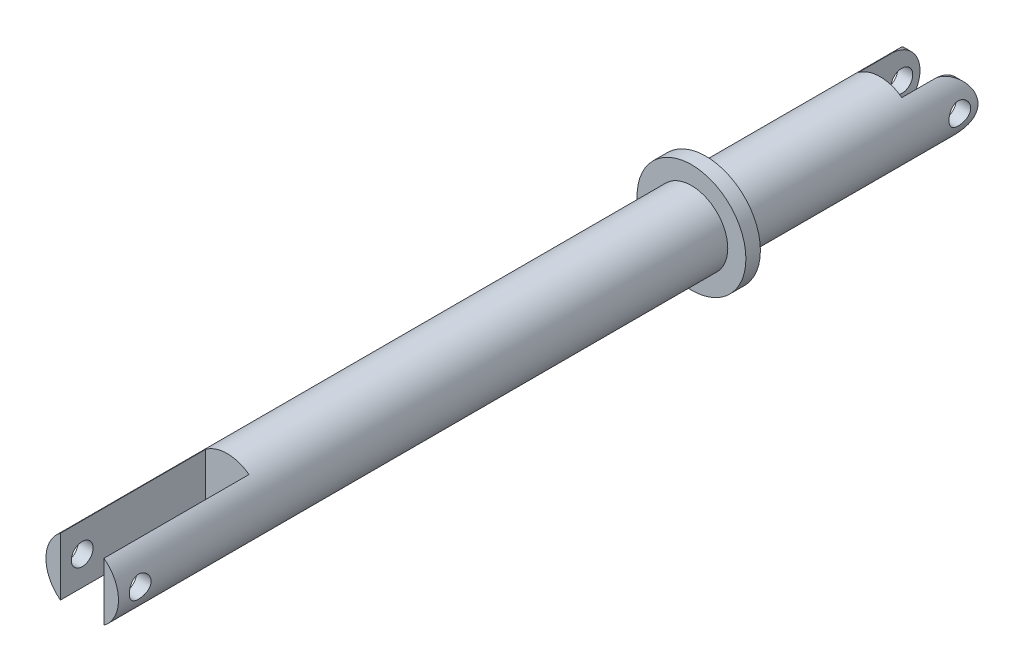
SolidWorks part; units mm, degrees
material "AISI 4340 Acero normalizado"
ref_plane "Alzado" through (0, 0, 0) normal (0, 0, 1) x (1, 0, 0)
ref_plane "Planta" through (0, 0, 0) normal (0, 1, 0) x (1, 0, 0)
ref_plane "Vista lateral" through (0, 0, 0) normal (1, 0, 0) x (0, 0, -1)
sketch "Croquis1" plane through (0, 0, 0) normal (0, 0, 1) x (1, 0, 0)
  circle A0 centre (0, 0) radius 2.5
extrude "Saliente-Extruir1" add sketch "Croquis1" along normal blind 60
ref_plane "Plano1" through (0, 0, 18) normal (0, 0, 1) x (1, 0, 0)
sketch "Croquis2" plane through (0, 0, 18) normal (0, 0, 1) x (1, 0, 0)
  circle A0 centre (0, 0) radius 2.5
  circle A1 centre (0, 0) radius 3.75
extrude "Saliente-Extruir2" add sketch "Croquis2" against normal blind 1
ref_plane "Plano2" through (0, 0, 60) normal (0, 0, 1) x (1, 0, 0)
sketch "Croquis5" plane through (0, 0, 60) normal (0, 0, 1) x (1, 0, 0)
  line L1 (1.5, -2.8348) -> (-1.5, -2.8348)
  line L2 (1.5, -2.8348) -> (1.5, 2.8348)
  line L3 (1.5, 2.8348) -> (-1.5, 2.8348)
  line L4 (-1.5, -2.8348) -> (-1.5, 2.8348)
  line L5 (1.5, -2.8348) -> (-1.5, 2.8348) construction
  line L6 (1.5, 2.8348) -> (-1.5, -2.8348) construction
  point P0 (0, 0)
extrude "Cortar-Extruir1" cut sketch "Croquis5" against normal mid plane 20
sketch "Croquis6" plane through (1.5, 0, 0) normal (-1, 0, 0) x (0, 0, 1)
  line L1 (60, -0.55) -> (60, 0.55) construction
  circle A2 centre (58.5, 0) radius 0.75
  dimension "D1" = 1.5
extrude "Cortar-Extruir2" cut sketch "Croquis6" against normal mid plane 9
sketch "Croquis7" plane through (0, 0, 0) normal (0, 0, -1) x (-1, 0, 0)
  line L1 (1.5, -3.2838) -> (-1.5, -3.2838)
  line L2 (1.5, -3.2838) -> (1.5, 3.2838)
  line L3 (1.5, 3.2838) -> (-1.5, 3.2838)
  line L4 (-1.5, -3.2838) -> (-1.5, 3.2838)
  line L5 (1.5, -3.2838) -> (-1.5, 3.2838) construction
  line L6 (1.5, 3.2838) -> (-1.5, -3.2838) construction
  point P0 (0, 0)
extrude "Cortar-Extruir3" cut sketch "Croquis7" against normal blind 5
sketch "Croquis8" plane through (1.5, 0, 0) normal (-1, 0, 0) x (0, 0, 1)
  circle A0 centre (2, 0) radius 0.75
extrude "Cortar-Extruir4" cut sketch "Croquis8" against normal mid plane 10
sketch "Croquis9" plane through (1.5, 0, 0) normal (-1, 0, 0) x (0, 0, 1)
  line L0 (0, 2) -> (2.75, 2)
  line L1 (0, 2) -> (0, -2)
  line L2 (0, -2) -> (2.75, -2)
  arc A0 (2.75, 2) -> (2.75, -2) centre (2.75, 0) ccw
  circle A1 centre (2, 0) radius 0.75 construction
extrude "Cortar-Extruir5" cut sketch "Croquis9" against normal mid plane 10
